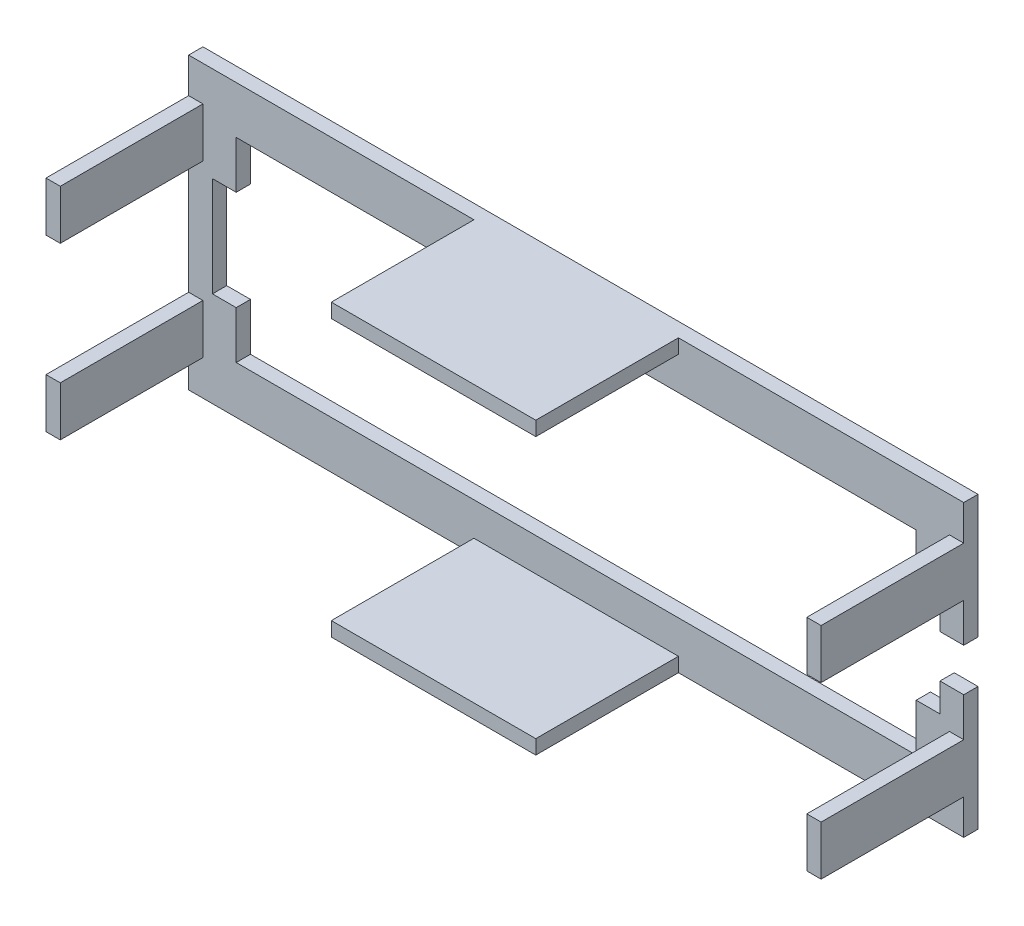
SolidWorks part; units mm, degrees
ref_plane "Front Plane" through (0, 0, 0) normal (0, 0, 1) x (1, 0, 0)
ref_plane "Top Plane" through (0, 0, 0) normal (0, 1, 0) x (1, 0, 0)
ref_plane "Right Plane" through (0, 0, 0) normal (1, 0, 0) x (0, 0, -1)
sketch "Sketch1" plane through (0, 0, 0) normal (0, 0, 1) x (1, 0, 0)
  line L0 (0, 0) -> (81.5, 0)
  line L1 (81.5, 0) -> (81.5, 13)
  line L2 (81.5, 30.5) -> (0, 30.5)
  line L3 (0, 30.5) -> (0, 0)
  line L4 (76.5, 5) -> (76.5, 10)
  line L5 (76.5, 25.5) -> (5, 25.5)
  line L6 (5, 25.5) -> (5, 20.5)
  line L7 (5, 5) -> (76.5, 5)
  line L8 (76.5, 10) -> (79, 10)
  line L9 (79, 10) -> (79, 13)
  line L10 (79, 20.5) -> (76.5, 20.5)
  line L11 (76.5, 20.5) -> (76.5, 25.5)
  line L12 (5, 10) -> (2.5, 10)
  line L13 (2.5, 10) -> (2.5, 20.5)
  line L14 (2.5, 20.5) -> (5, 20.5)
  line L15 (5, 10) -> (5, 5)
  line L16 (81.5, 13) -> (79, 13)
  line L17 (79, 17.5) -> (81.5, 17.5)
  line L18 (81.5, 17.5) -> (81.5, 30.5)
  line L19 (79, 17.5) -> (79, 20.5)
  dimension "D1" = 30.5
  dimension "D2" = 81.5
  dimension "D3" = 5
  dimension "D4" = 5
  dimension "D5" = 5
  dimension "D6" = 5
  dimension "D7" = 2.5
  dimension "D8" = 10
  dimension "D9" = 10
  dimension "D10" = 2.5
  dimension "D11" = 10
  dimension "D12" = 13
  dimension "D13" = 13
extrude "Boss-Extrude1" add sketch "Sketch1" along normal blind 1.5
sketch "Sketch2" plane through (0, 0, 1.5) normal (0, 0, 1) x (1, 0, 0)
  line L0 (0, 26.8) -> (0, 21.6)
  line L1 (30, 0) -> (51.5, 0)
  line L2 (81.5, 3.7) -> (81.5, 8.9)
  line L5 (51.5, 30.5) -> (30, 30.5)
  line L6 (1.5, 26.8) -> (1.5, 21.6)
  line L7 (30, 1.5) -> (51.5, 1.5)
  line L8 (80, 3.7) -> (80, 8.9)
  line L9 (51.5, 29) -> (30, 29)
  line L10 (80, 26.8) -> (81.5, 26.8)
  line L11 (80, 21.6) -> (81.5, 21.6)
  line L12 (80, 8.9) -> (81.5, 8.9)
  line L13 (80, 3.7) -> (81.5, 3.7)
  line L14 (0, 26.8) -> (1.5, 26.8)
  line L15 (0, 21.6) -> (1.5, 21.6)
  line L16 (0, 8.9) -> (1.5, 8.9)
  line L17 (0, 3.7) -> (1.5, 3.7)
  line L18 (80, 21.6) -> (80, 26.8)
  line L19 (81.5, 21.6) -> (81.5, 26.8)
  line L20 (1.5, 8.9) -> (1.5, 3.7)
  line L21 (0, 8.9) -> (0, 3.7)
  line L22 (30, 1.5) -> (30, 0)
  line L23 (51.5, 1.5) -> (51.5, 0)
  line L24 (30, 29) -> (30, 30.5)
  line L25 (51.5, 30.5) -> (51.5, 29)
  line L26 (81.5, 30.5) -> (0, 30.5) construction
  line L27 (81.5, 0) -> (81.5, 13) construction
  dimension "D1" = 1.5
  dimension "D2" = 1.5
  dimension "D3" = 1.5
  dimension "D4" = 1.5
  dimension "D5" = 3.7
  dimension "D6" = 5.2
  dimension "D7" = 3.7
  dimension "D8" = 5.2
  dimension "D9" = 3.7
  dimension "D10" = 5.2
  dimension "D11" = 3.7
  dimension "D12" = 5.2
  dimension "D13" = 30
  dimension "D14" = 30
  dimension "D15" = 30
  dimension "D16" = 30
  dimension "D17" = 0
  dimension "D18" = 0
extrude "Boss-Extrude2" add sketch "Sketch2" along normal blind 15
